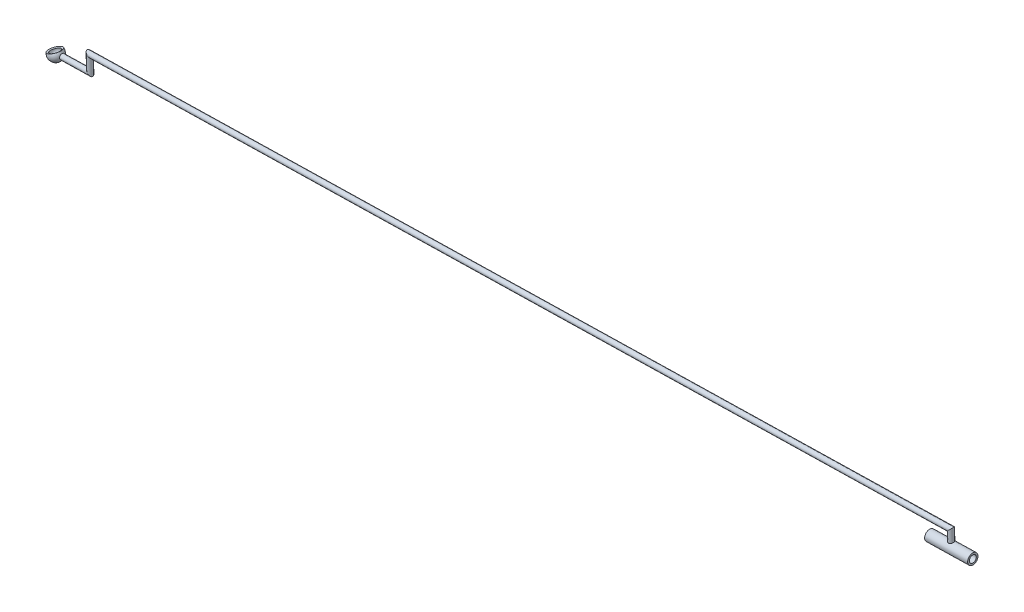
SolidWorks part; units mm, degrees
ref_plane "Plan de face" through (0, 0, 0) normal (0, 0, 1) x (1, 0, 0)
ref_plane "Plan de dessus" through (0, 0, 0) normal (0, 1, 0) x (1, 0, 0)
ref_plane "Plan de droite" through (0, 0, 0) normal (1, 0, 0) x (0, 0, -1)
sketch "Esquisse2" plane through (0, 0, 0) normal (0, 0, 1) x (1, 0, 0)
  line L0 (-993, -170) -> (-973.005, -169.5536)
  line L1 (-973.005, -169.5536) -> (-973.2059, -160.5559)
  line L2 (-973.2059, -160.5559) -> (-473.3304, -149.3964)
  line L3 (-473.3304, -149.3964) -> (-473.1965, -155.3949)
  line L4 (-485.6934, -155.6739) -> (-460.6996, -155.1159)
  line L5 (-485.5595, -161.6724) -> (-460.5657, -161.1144)
  line L6 (-993, -170) -> (-291.1616, -154.3318) construction
  point P10 (-473.0626, -161.3934)
  dimension "D2" = 20
  dimension "D3" = 6
  dimension "D4" = 6
  dimension "D5" = 500
  dimension "D7" = 25
sketch "Esquisse3" plane through (0, 0, 0) normal (0, 0, 1) x (1, 0, 0)
  line L0 (-485.6264, -158.6731) -> (-485.6934, -155.6739)
  line L1 (-993, -170) -> (-291.1616, -154.3318) construction
  line L2 (-485.6934, -155.6739) -> (-460.6996, -155.1159)
  line L3 (-460.6996, -155.1159) -> (-460.6326, -158.1152)
  line L4 (-460.6326, -158.1152) -> (-485.6264, -158.6731)
  line L5 (-485.6264, -158.6731) -> (-460.6326, -158.1152) construction
revolve "Révolution1" add sketch "Esquisse3" angle 360 about L5
sketch "Esquisse4" plane through (0, 0, 0) normal (0, 0, 1) x (1, 0, 0)
  line L0 (-990.0007, -169.933) -> (-973.005, -169.5536)
  line L1 (-993, -170) -> (-973.005, -169.5536) construction
  line L2 (-973.005, -169.5536) -> (-973.2059, -160.5559)
  line L3 (-973.2059, -160.5559) -> (-473.3304, -149.3964)
  line L4 (-473.3304, -149.3964) -> (-473.1295, -158.3942)
  line L5 (-993, -170) -> (-291.1616, -154.3318) construction
  circle A0 centre (-993, -170) radius 3 construction
ref_plane "Plan1" through (-990.0007, -169.933, 0) normal (0.9998, 0.0223, 0) x (0, 0, -1)
sketch "Esquisse5" plane through (-990.0007, -169.933, 0) normal (0.9998, 0.0223, 0) x (0, 0, -1)
  circle A0 centre (0, 0) radius 1.5
  dimension "D1" = 3
sweep "Balayage1" add profiles "Esquisse5" path "Esquisse4"
sketch "Esquisse6" plane through (-488.925, -10.915, 0) normal (-0.9998, -0.0223, 0) x (0, 0, 1)
  circle A2 centre (0, -147.7949) radius 2
  circle A3 centre (0, -147.7949) radius 2
  dimension "D1" = 1
extrude "Enlèv. mat.-Extru.1" cut sketch "Esquisse6" against normal through all
sketch "Esquisse7" plane through (0, 0, 0) normal (0, 0, 1) x (1, 0, 0)
  line L0 (-993, -170) -> (-990.2045, -168.9113) construction
  line L1 (-993, -170) -> (-973.005, -169.5536) construction
  line L2 (-994.0887, -167.2045) -> (-991.9113, -172.7955) construction
  circle A1 centre (-993, -170) radius 3 construction
  arc A2 (-991.9113, -172.7955) -> (-990.7177, -168.053) centre (-993, -170) ccw
  dimension "D1" = 1
  dimension "D3" = 20
revolve "Révol.-Mince2" add sketch "Esquisse7" angle 360 about L2
